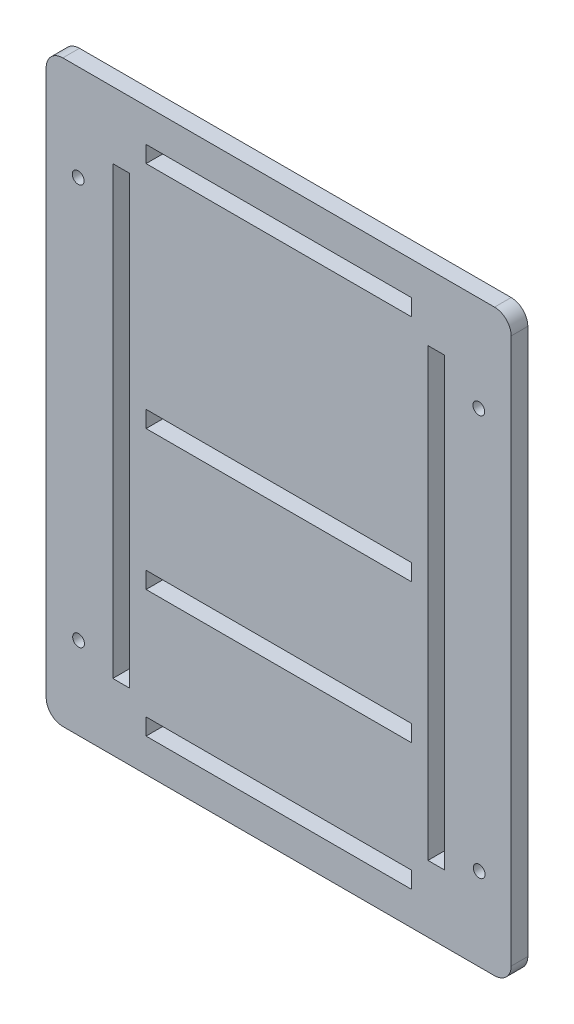
SolidWorks part; units mm, degrees
material "Acrylic (Medium-high impact)"
ref_plane "Front Plane" through (0, 0, 0) normal (0, 0, 1) x (1, 0, 0)
ref_plane "Top Plane" through (0, 0, 0) normal (0, 1, 0) x (1, 0, 0)
ref_plane "Right Plane" through (0, 0, 0) normal (1, 0, 0) x (0, 0, -1)
sketch "Sketch1" plane through (0, 0, 0) normal (0, 0, 1) x (1, 0, 0)
  line L0 (-107.5182, 189.1227) -> (-6.35, 189.1227) construction
  line L1 (-6.35, 189.1227) -> (-6.35, 195.4727) construction
  line L2 (-6.35, 195.4727) -> (-107.5182, 195.4727) construction
  line L3 (-107.5182, 195.4727) -> (-107.5182, 189.1227) construction
  line L4 (-126.5682, 0) -> (-126.5682, 195.4727) construction
  line L5 (25.4, -12.7) -> (-139.2682, -12.7)
  line L6 (31.75, -6.35) -> (31.75, 201.8227)
  line L7 (25.4, 208.1727) -> (-139.2682, 208.1727)
  line L8 (-145.6182, -6.35) -> (-145.6182, 201.8227)
  line L9 (12.7, 195.4727) -> (12.7, 0) construction
  line L10 (6.35, -6.35) -> (-120.2182, -6.35) construction
  line L11 (-120.2182, 201.8227) -> (6.35, 201.8227) construction
  line L12 (0, 182.7727) -> (0, 12.7) construction
  line L13 (0, 12.7) -> (6.35, 12.7) construction
  line L14 (6.35, 12.7) -> (6.35, 182.7727) construction
  line L15 (6.35, 182.7727) -> (0, 182.7727) construction
  line L16 (-113.8682, 12.7) -> (-113.8682, 182.7727) construction
  line L17 (-113.8682, 182.7727) -> (-120.2182, 182.7727) construction
  line L18 (-120.2182, 182.7727) -> (-120.2182, 12.7) construction
  line L19 (-120.2182, 12.7) -> (-113.8682, 12.7) construction
  line L20 (-107.5182, 101.6) -> (-6.35, 101.6) construction
  line L21 (-6.35, 101.6) -> (-6.35, 107.95) construction
  line L22 (-6.35, 107.95) -> (-107.5182, 107.95) construction
  line L23 (-107.5182, 107.95) -> (-107.5182, 101.6) construction
  line L24 (-107.5182, 0) -> (-6.35, 0) construction
  line L25 (-6.35, 0) -> (-6.35, 6.35) construction
  line L26 (-6.35, 6.35) -> (-107.5182, 6.35) construction
  line L27 (-107.5182, 6.35) -> (-107.5182, 0) construction
  line L28 (-107.5182, 189.1227) -> (-6.35, 189.1227)
  line L29 (-6.35, 189.1227) -> (-6.35, 195.4727)
  line L30 (-6.35, 195.4727) -> (-107.5182, 195.4727)
  line L31 (-107.5182, 195.4727) -> (-107.5182, 189.1227)
  line L32 (0, 182.7727) -> (0, 12.7)
  line L33 (0, 12.7) -> (6.35, 12.7)
  line L34 (6.35, 12.7) -> (6.35, 182.7727)
  line L35 (6.35, 182.7727) -> (0, 182.7727)
  line L36 (-113.8682, 12.7) -> (-113.8682, 182.7727)
  line L37 (-113.8682, 182.7727) -> (-120.2182, 182.7727)
  line L38 (-120.2182, 182.7727) -> (-120.2182, 12.7)
  line L39 (-120.2182, 12.7) -> (-113.8682, 12.7)
  line L40 (-107.5182, 101.6) -> (-6.35, 101.6)
  line L41 (-6.35, 101.6) -> (-6.35, 107.95)
  line L42 (-6.35, 107.95) -> (-107.5182, 107.95)
  line L43 (-107.5182, 107.95) -> (-107.5182, 101.6)
  line L44 (-107.5182, 0) -> (-6.35, 0)
  line L45 (-6.35, 0) -> (-6.35, 6.35)
  line L46 (-6.35, 6.35) -> (-107.5182, 6.35)
  line L47 (-107.5182, 6.35) -> (-107.5182, 0)
  line L52 (-107.5182, 48.4378) -> (-6.35, 48.4378)
  line L53 (-6.35, 48.4378) -> (-6.35, 54.7878)
  line L54 (-6.35, 54.7878) -> (-107.5182, 54.7878)
  line L55 (-107.5182, 54.7878) -> (-107.5182, 48.4378)
  line L56 (-107.5182, 48.4378) -> (-6.35, 48.4378)
  line L57 (-6.35, 48.4378) -> (-6.35, 54.7878)
  line L58 (-6.35, 54.7878) -> (-107.5182, 54.7878)
  line L59 (-107.5182, 54.7878) -> (-107.5182, 48.4378)
  arc A0 (31.75, 201.8227) -> (25.4, 208.1727) centre (25.4, 201.8227) ccw
  arc A1 (25.4, -12.7) -> (31.75, -6.35) centre (25.4, -6.35) ccw
  arc A2 (-139.2682, -12.7) -> (-145.6182, -6.35) centre (-139.2682, -6.35) cw
  arc A3 (-139.2682, 208.1727) -> (-145.6182, 201.8227) centre (-139.2682, 201.8227) ccw
  dimension "D6" = 6.35
  dimension "D1" = 19.05
  dimension "D3" = 19.05
  dimension "D4" = 6.35
  dimension "D5" = 6.35
  dimension "D2" = 0
extrude "Boss-Extrude1" add sketch "Sketch1" along normal blind 6.35
hole_wizard "#8 Clearance Hole1" positions "Sketch3" profile "Sketch4" hole size "#8" standard "ANSI Inch" end condition through all
sketch "Sketch3" plane through (-70.641, 181.5368, 9.525) normal (0, 0, -1) x (-1, 0, 0)
  point P0 (62.6252, -162.7658)
  point P3 (62.7721, -9.9546)
  point P6 (-90.0391, -9.8077)
  point P9 (-90.186, -162.6189)
sketch "Sketch4" plane through (-133.2663, 18.771, 9.525) normal (1, 0, 0) x (0, -1, 0)
  line L0 (0, 0) -> (0, 9.525)
  line L1 (0, 9.525) -> (2.2479, 9.525)
  line L2 (2.2479, 9.525) -> (2.2479, 0)
  line L3 (2.2479, 0) -> (0, 0)
  line L4 (0, -6.35) -> (0, 107.95) construction
  dimension "Thru Hole Dia." = 4.4958
  dimension "Thru Hole Depth" = 9.525
